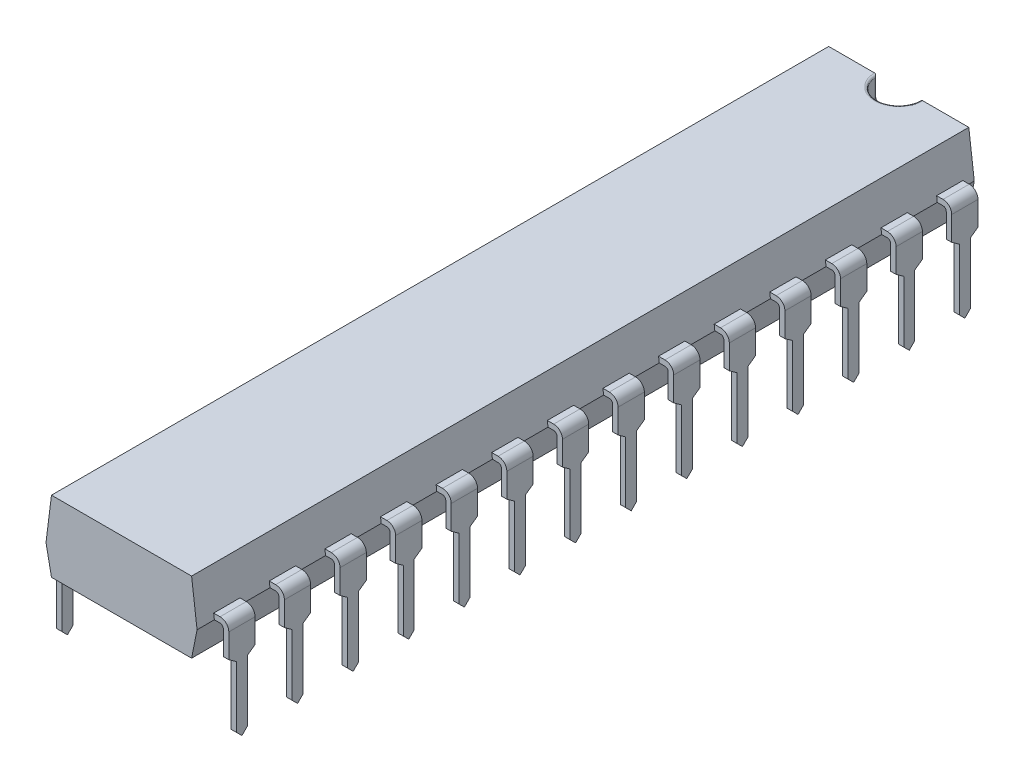
SolidWorks part; units mm, degrees
ref_plane "Plan de face" through (0, 0, 0) normal (0, 0, 1) x (1, 0, 0)
ref_plane "Plan de dessus" through (0, 0, 0) normal (0, 1, 0) x (1, 0, 0)
ref_plane "Plan de droite" through (0, 0, 0) normal (1, 0, 0) x (0, 0, -1)
sketch "Esquisse1" plane through (0, 0, 0) normal (0, 0, 1) x (1, 0, 0)
  line L0 (-3.45, -0.375) -> (-3.2, -1.625)
  line L1 (-3.2, -1.625) -> (3.2, -1.625)
  line L2 (0, 0) -> (0, 0.8004) construction
  line L3 (-3.2, 1.625) -> (3.2, 1.625)
  line L5 (-3.2215, -1.5174) -> (3.2139, 1.5138) construction
  line L6 (-3.2139, 1.5138) -> (3.2215, -1.5174) construction
  line L7 (-3.45, -0.375) -> (-3.2, 1.625)
  line L8 (3.45, -0.375) -> (3.2, -1.625)
  line L9 (3.45, -0.375) -> (3.2, 1.625)
  point P0 (0, 0)
  dimension "D1" = 1.25
  dimension "D4" = 3.2
  dimension "D5" = 3.2
extrude "Boss.-Extru.1" add sketch "Esquisse1" along normal blind 35.5
ref_plane "Plan1" through (0, 0, 1.09) normal (0, 0, 1) x (1, 0, 0)
sketch "Esquisse3" plane through (0, 0, 1.09) normal (0, 0, 1) x (1, 0, 0)
  line L0 (3.1859, -0.375) -> (3.71, -0.375)
  line L1 (3.86, -0.525) -> (3.86, -4.925)
  line L2 (-3.2, -1.625) -> (3.2, -1.625) construction
  line L3 (3.1859, -0.125) -> (3.71, -0.125)
  line L4 (4.11, -0.525) -> (4.11, -4.925)
  line L5 (3.1859, -0.125) -> (3.1859, -0.375)
  line L6 (3.45, -0.125) -> (3.71, -0.125) construction
  line L7 (3.45, -0.375) -> (3.71, -0.375) construction
  line L8 (3.86, -4.925) -> (4.11, -4.925)
  arc A0 (3.71, -0.375) -> (3.86, -0.525) centre (3.71, -0.525) cw
  arc A1 (3.71, -0.125) -> (4.11, -0.525) centre (3.71, -0.525) cw
  point P7 (3.86, -0.375)
  dimension "D2" = 0.15
  dimension "D1" = 0.66
  dimension "D3" = 3.3
  dimension "D4" = 0.25
extrude "Boss.-Extru.2" add sketch "Esquisse3" along normal mid plane 1.2
sketch "Esquisse4" plane through (4.11, 0, 0) normal (1, 0, 0) x (0, 0, -1)
  line L0 (-1.09, -4.925) -> (-1.09, -1.875) construction
  line L1 (-1.69, -4.925) -> (-0.49, -4.925) construction
  line L2 (-1.34, -4.675) -> (-0.2229, -4.675) construction
  line L3 (-1.34, -4.675) -> (-1.34, -1.875)
  line L4 (-1.34, -1.875) -> (-1.69, -1.625)
  line L5 (-35.5, -1.625) -> (0, -1.625) construction
  line L6 (-1.69, -4.925) -> (-1.69, -0.525) construction
  line L7 (-1.69, -1.625) -> (-1.907, -1.625)
  line L8 (-1.907, -1.625) -> (-1.907, -4.925)
  line L9 (-1.907, -4.925) -> (-1.09, -4.925)
  line L10 (-1.34, -4.675) -> (-1.09, -4.925)
  line L12 (-1.34, -4.925) -> (-1.34, -1.875) construction
  dimension "D1" = 3.05
  dimension "D2" = 0.25
  dimension "D3" = 0.25
extrude "Enlèv. mat.-Extru.1" cut sketch "Esquisse4" against normal blind 0.5
mirror "Symétrie1" about plane through (0, 0, 1.09) normal (0, 0, 1) of "Enlèv. mat.-Extru.1"
pattern_linear "Répétition linéaire1" count 14 spacing 2.54 along (0, 0, 1) of "Symétrie1", "Enlèv. mat.-Extru.1", "Boss.-Extru.2"
mirror "Symétrie2" about plane through (0, 0, 0) normal (1, 0, 0) of "Répétition linéaire1", "Boss.-Extru.2", "Enlèv. mat.-Extru.1", "Symétrie1"
sketch "Esquisse5" plane through (0, 1.625, 0) normal (0, 1, 0) x (1, 0, 0)
  circle A0 centre (0, 0) radius 1
  dimension "D1" = 2
extrude "Enlèv. mat.-Extru.2" cut sketch "Esquisse5" against normal blind 1
fillet "Congé2" radius 0.1 5 edges at (0, 0.625, 0) (0, 0.625, 1) (-1, 1.125, 0) (1, 1.125, 0) (0, 1.625, 1)
